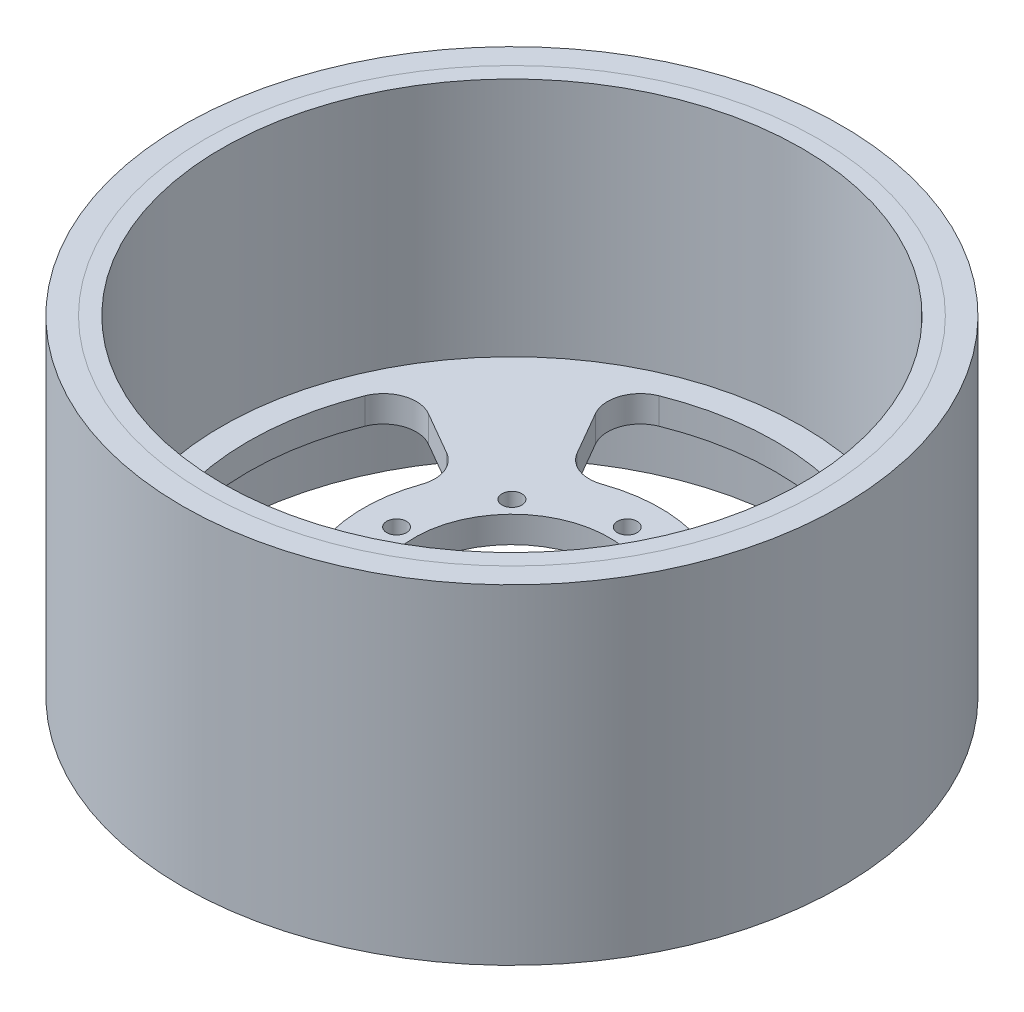
SolidWorks part; units mm, degrees
material "7050-T73510"
ref_plane "前视基准面" through (0, 0, 0) normal (0, 0, 1) x (1, 0, 0)
ref_plane "上视基准面" through (0, 0, 0) normal (0, 1, 0) x (1, 0, 0)
ref_plane "右视基准面" through (0, 0, 0) normal (1, 0, 0) x (0, 0, -1)
sketch "草图1" plane through (0, 0, 0) normal (0, 1, 0) x (1, 0, 0)
  circle A0 centre (0, 0) radius 50
  dimension "D1" = 100
extrude "凸台-拉伸1" add sketch "草图1" along normal blind 50
sketch "草图2" plane through (0, 50, 0) normal (0, 1, 0) x (1, 0, 0)
  circle A0 centre (0, 0) radius 44
  dimension "D1" = 88
extrude "切除-拉伸1" cut sketch "草图2" against normal blind 36.5
sketch "草图3" plane through (0, 0, 0) normal (0, -1, 0) x (1, 0, 0)
  circle A0 centre (0, 0) radius 44
  dimension "D1" = 88
extrude "切除-拉伸2" cut sketch "草图3" against normal blind 9.5
sketch "草图4" plane through (0, 13.5, 0) normal (0, 1, 0) x (1, 0, 0)
  circle A0 centre (0, 0) radius 14.75
  circle A1 centre (0, 0) radius 17.5 construction
  circle A2 centre (0, 17.5) radius 1.5
  circle A3 centre (12.3744, 12.3744) radius 1.5
  circle A4 centre (17.5, 0) radius 1.5
  circle A5 centre (12.3744, -12.3744) radius 1.5
  circle A6 centre (0, -17.5) radius 1.5
  circle A7 centre (-12.3744, -12.3744) radius 1.5
  circle A8 centre (-17.5, 0) radius 1.5
  circle A9 centre (-12.3744, 12.3744) radius 1.5
  point P22 (0, 0)
  dimension "D1" = 29.5
  dimension "D2" = 35
  dimension "D3" = 3
extrude "切除-拉伸3" cut sketch "草图4" against normal blind 4
sketch "草图5" plane through (0, 50, 0) normal (0, 1, 0) x (1, 0, 0)
  circle A0 centre (0, 0) radius 46.5
  dimension "D1" = 93
split line "分割线1"
sketch "草图7" plane through (0, 50, 0) normal (0, 1, 0) x (1, 0, 0)
  circle A0 centre (0, 0) radius 46.5
  dimension "D1" = 93
split line "分割线2"
sketch "草图8" plane through (0, 13.5, 0) normal (0, 1, 0) x (1, 0, 0)
  line L0 (0, 0) -> (0, 40) construction
  line L1 (-11.25, 19.4856) -> (-20, 34.641)
  line L2 (-11.25, 19.4856) -> (0, 0) construction
  line L3 (11.25, 19.4856) -> (20, 34.641)
  line L4 (19.4856, 11.25) -> (34.641, 20)
  line L5 (19.4856, -11.25) -> (34.641, -20)
  line L6 (11.25, -19.4856) -> (20, -34.641)
  line L7 (-11.25, -19.4856) -> (-20, -34.641)
  line L8 (-19.4856, -11.25) -> (-34.641, -20)
  line L9 (-19.4856, 11.25) -> (-34.641, 20)
  arc A0 (20, 34.641) -> (-20, 34.641) centre (0, 0) ccw
  arc A1 (11.25, 19.4856) -> (-11.25, 19.4856) centre (0, 0) ccw
  arc A2 (-19.4856, 11.25) -> (-19.4856, -11.25) centre (0, 0) ccw
  arc A3 (-34.641, 20) -> (-34.641, -20) centre (0, 0) ccw
  arc A4 (-11.25, -19.4856) -> (11.25, -19.4856) centre (0, 0) ccw
  arc A5 (-20, -34.641) -> (20, -34.641) centre (0, 0) ccw
  arc A6 (19.4856, -11.25) -> (19.4856, 11.25) centre (0, 0) ccw
  arc A7 (34.641, -20) -> (34.641, 20) centre (0, 0) ccw
  point P24 (0, 0)
  dimension "D1" = 80
  dimension "D2" = 45
  dimension "D3" = 30
extrude "切除-拉伸4" cut sketch "草图8" against normal blind 4
fillet "圆角1" radius 5 16 edges at (34.641, 11.5, -20) (34.641, 11.5, 20) (19.4856, 11.5, 11.25) (19.4856, 11.5, -11.25) (11.25, 11.5, -19.4856) (-11.25, 11.5, -19.4856) (-19.4856, 11.5, -11.25) (-19.4856, 11.5, 11.25) (-11.25, 11.5, 19.4856) (11.25, 11.5, 19.4856) (20, 11.5, 34.641) (-20, 11.5, 34.641) (-34.641, 11.5, 20) (-34.641, 11.5, -20) (-20, 11.5, -34.641) (20, 11.5, -34.641)
